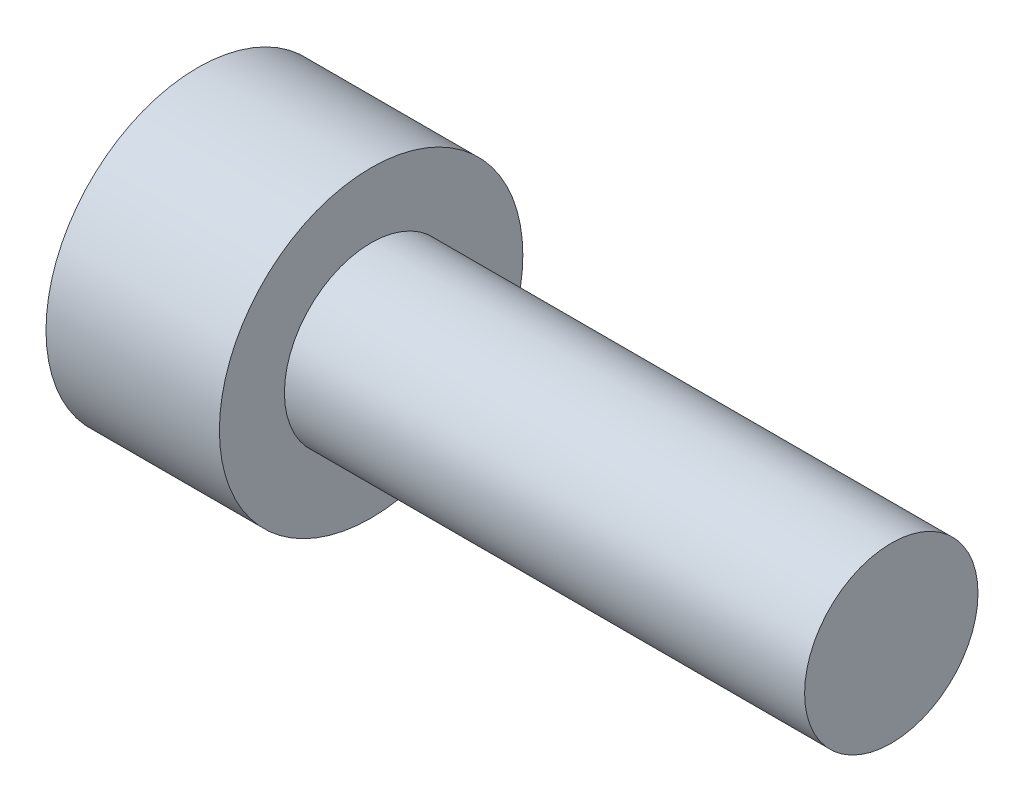
SolidWorks part; units mm, degrees
material "AISI 304"
ref_plane "Front Plane" through (0, 0, 0) normal (0, 0, 1) x (1, 0, 0)
ref_plane "Top Plane" through (0, 0, 0) normal (0, 1, 0) x (1, 0, 0)
ref_plane "Right Plane" through (0, 0, 0) normal (1, 0, 0) x (0, 0, -1)
sketch "草图1" plane through (0, 0, 0) normal (1, 0, 0) x (0, 0, -1)
  circle A0 centre (0, 0) radius 3.5
  dimension "D1" = 7
extrude "凸台-拉伸1" add sketch "草图1" along normal blind 4
sketch "草图2" plane through (0, 0, 0) normal (-1, 0, 0) x (0, 0, 1)
  line L1 (1.525, -0.8805) -> (1.525, 0.8805)
  line L2 (1.525, 0.8805) -> (0, 1.7609)
  line L3 (0, 1.7609) -> (-1.525, 0.8805)
  line L4 (-1.525, 0.8805) -> (-1.525, -0.8805)
  line L5 (-1.525, -0.8805) -> (0, -1.7609)
  line L6 (0, -1.7609) -> (1.525, -0.8805)
  circle A0 centre (0, 0) radius 1.525 construction
  dimension "D1" = 3.05
extrude "切除-拉伸1" cut sketch "草图2" against normal blind 2
sketch "草图3" plane through (4, 0, 0) normal (1, 0, 0) x (0, 0, -1)
  circle A0 centre (0, 0) radius 2
  dimension "D1" = 4
extrude "凸台-拉伸2" add sketch "草图3" along normal blind 12
cosmetic thread "装饰螺纹线1" parameters "D2"=4
